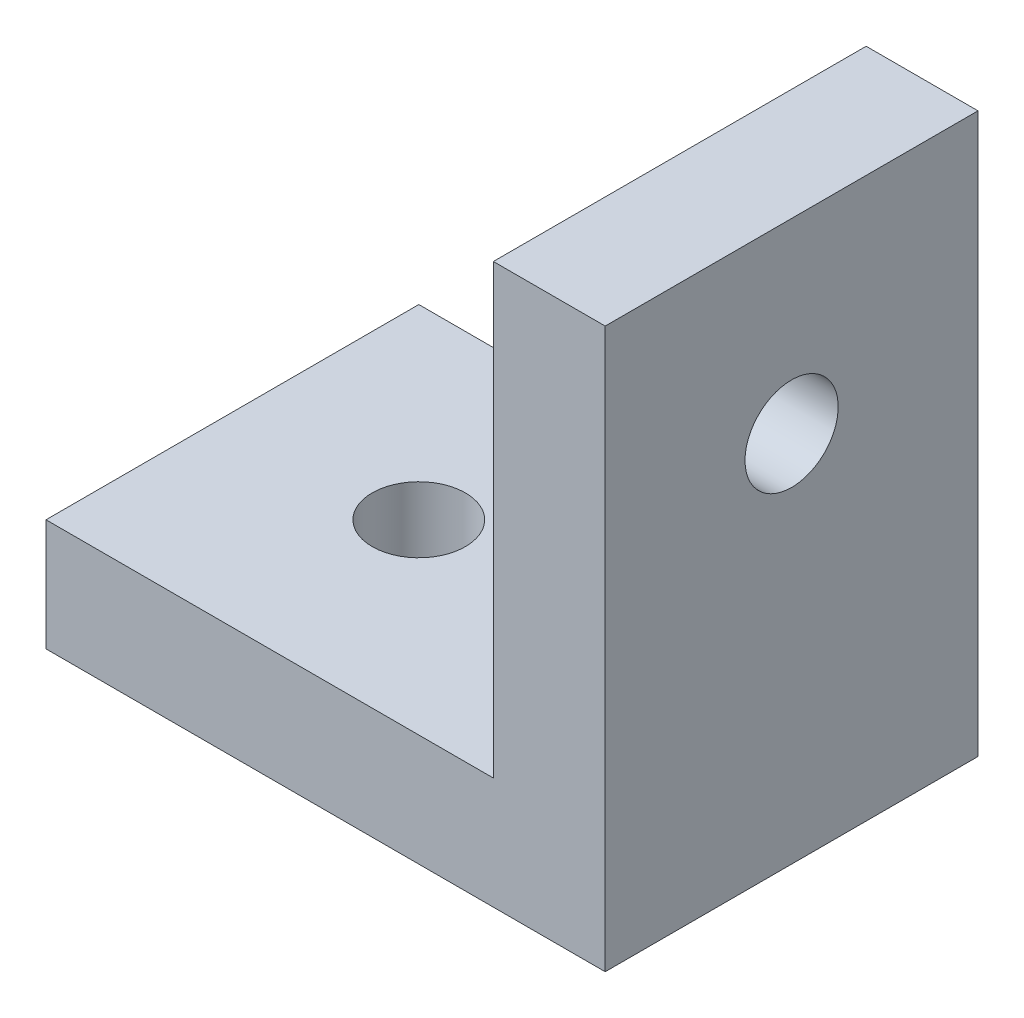
SolidWorks part; units mm, degrees
ref_plane "前基準面" through (0, 0, 0) normal (0, 0, 1) x (1, 0, 0)
ref_plane "上基準面" through (0, 0, 0) normal (0, 1, 0) x (1, 0, 0)
ref_plane "右基準面" through (0, 0, 0) normal (1, 0, 0) x (0, 0, -1)
sketch "草圖1" plane through (0, 0, 0) normal (0, 1, 0) x (1, 0, 0)
  line L1 (-7.5, 5) -> (7.5, 5)
  line L2 (-7.5, 5) -> (-7.5, -5)
  line L3 (-7.5, -5) -> (7.5, -5)
  line L4 (7.5, 5) -> (7.5, -5)
  line L5 (-7.5, 5) -> (7.5, -5) construction
  line L6 (-7.5, -5) -> (7.5, 5) construction
  point P0 (0, 0)
  dimension "D1" = 15
  dimension "D2" = 10
extrude "填料-伸長1" add sketch "草圖1" along normal blind 3
sketch "草圖2" plane through (0, 3, 0) normal (0, 1, 0) x (1, 0, 0)
  line L0 (-7.5, -5) -> (7.5, -5) construction
  line L1 (7.5, 5) -> (4.5, 5)
  line L2 (7.5, 5) -> (7.5, -5)
  line L3 (7.5, -5) -> (4.5, -5)
  line L4 (4.5, 5) -> (4.5, -5)
  dimension "D1" = 3
extrude "填料-伸長2" add sketch "草圖2" along normal blind 12
sketch "草圖3" plane through (4.5, 0, 0) normal (-1, 0, 0) x (0, 0, 1)
  line L0 (-5, 15) -> (5, 15) construction
  line L1 (-5, 15) -> (-5, 3) construction
  point P0 (0, 10)
  dimension "D1" = 5
  dimension "D2" = 5
sketch "草圖4" plane through (0, 3, 0) normal (0, 1, 0) x (1, 0, 0)
  line L0 (-7.5, 5) -> (7.5, 5) construction
  line L1 (-7.5, 5) -> (-7.5, -5) construction
  point P0 (-2.5, 0)
  dimension "D1" = 5
  dimension "D2" = 5
hole_wizard "M3  螺絲攻的螺孔鑽1" positions "3D草圖1" profile "草圖5" hole size "M3" standard "GB" end condition through all
sketch3d "3D草圖1"
  point P0 (4.5, 10, 0)
  point P3 (-2.5, 3, 0)
sketch "草圖5" plane through (4.5, 10, 0) normal (0, 1, 0) x (0, 0, 1)
  line L0 (0, 0) -> (0, 3)
  line L1 (0, 3) -> (1.25, 3)
  line L2 (1.25, 3) -> (1.25, 0)
  line L5 (1.25, 0) -> (0, 0)
  line L11 (0, -6.35) -> (0, 107.95) construction
  dimension "貫穿孔直徑" = 2.5
  dimension "貫穿孔深度" = 3
